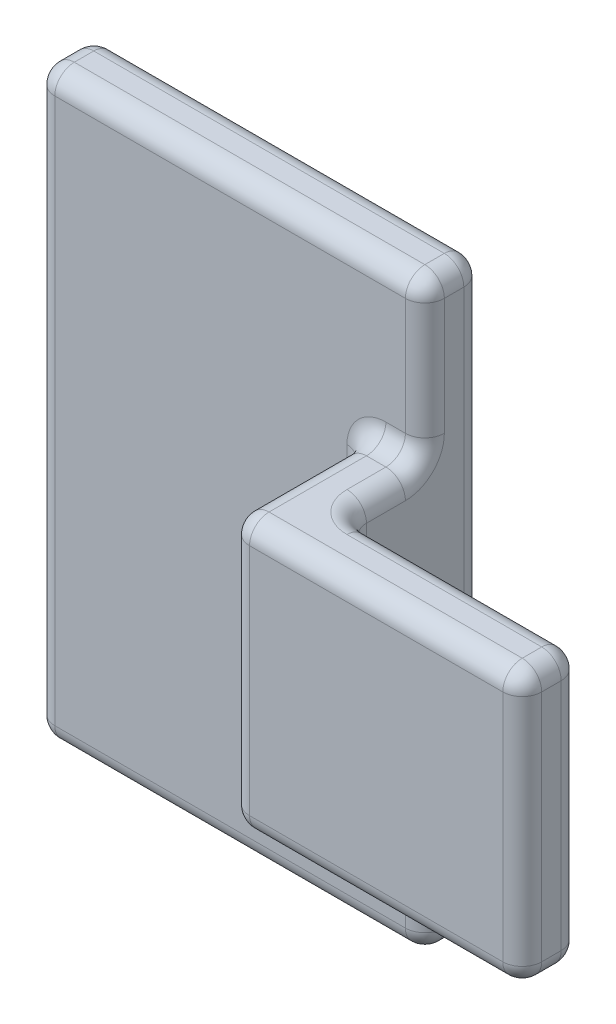
SolidWorks part; units mm, degrees
ref_plane "Front Plane" through (0, 0, 0) normal (0, 0, 1) x (1, 0, 0)
ref_plane "Top Plane" through (0, 0, 0) normal (0, 1, 0) x (1, 0, 0)
ref_plane "Right Plane" through (0, 0, 0) normal (1, 0, 0) x (0, 0, -1)
sketch "Sketch1" plane through (0, 0, 0) normal (0, 0, 1) x (1, 0, 0)
  line L0 (0, -30) -> (0, 0)
  line L3 (0, -30) -> (20, -30)
  line L4 (20, -30) -> (20, 0)
  line L5 (20, 0) -> (0, 0)
  line L6 (10, -7.5) -> (10, -22.5) construction
  line L7 (10, -15) -> (0, -15) construction
  line L8 (10, -15) -> (10, -30) construction
  circle A2 centre (10, -7.5) radius 2.25 construction
  circle A3 centre (10, -22.5) radius 2.25 construction
  dimension "D4" = 4.5
  dimension "D5" = 4.5
  dimension "D1" = 20
  dimension "D2" = 30
  dimension "D3" = 15
extrude "Boss-Extrude1" add sketch "Sketch1" along normal blind 3
ref_plane "Plane1" through (20, 0, 0) normal (-1, 0, 0) x (0, 0, 1)
sketch "Sketch3" plane through (20, 0, 0) normal (-1, 0, 0) x (0, 0, 1)
  line L0 (3, -8) -> (10, -8)
  line L1 (3, 0) -> (3, -30) construction
  line L2 (10, -8) -> (10, -22)
  line L3 (10, -22) -> (3, -22)
  line L4 (3, -22) -> (3, -8)
  dimension "D1" = 8
  dimension "D2" = 7
  dimension "D3" = 8
extrude "Boss-Extrude2" add sketch "Sketch3" along normal blind 3
sketch "Sketch4" plane through (17, 0, 0) normal (-1, 0, 0) x (0, 0, 1)
  line L0 (10, -8) -> (3, -8) construction
  line L1 (10, -22) -> (7, -22)
  line L2 (10, -22) -> (10, -8)
  line L3 (10, -8) -> (7, -8)
  line L4 (7, -22) -> (7, -8)
  dimension "D1" = 3
extrude "Boss-Extrude3" add sketch "Sketch4" against normal blind 15
ref_plane "Plane2" through (0, 0, 10) normal (0, 0, 1) x (1, 0, 0)
sketch "Sketch6" plane through (0, 0, 10) normal (0, 0, 1) x (1, 0, 0)
  line L1 (32, 14.1) -> (23, 14.1)
  line L2 (32, 14.1) -> (32, -44.1)
  line L3 (32, -44.1) -> (23, -44.1)
  line L4 (23, 14.1) -> (23, -44.1)
  dimension "D1" = 0
  dimension "D2" = 22.1
  dimension "D3" = 22.1
  dimension "D4" = 9
extrude "Boss-Extrude4" [suppressed] add sketch "Sketch6" against normal blind 2
sketch "Sketch7" [suppressed] plane through (0, 0, 21) normal (0, 0, -1) x (-1, 0, 0)
  line L2 (-38.6471, 43.1227) -> (-38.6471, 41.1227)
  line L5 (-38.6471, 43.1227) -> (-47.6471, 43.1227)
  line L6 (-47.6471, 43.1227) -> (-47.6471, 41.1227)
  line L7 (-47.6471, -35.8773) -> (-47.6471, 43.1227) construction
  line L8 (-47.6471, 41.1227) -> (-38.6471, 41.1227)
  dimension "D1" = 2
extrude "Boss-Extrude5" [suppressed] add sketch "Sketch7" along normal blind 18.4
sketch "Sketch9" [suppressed] plane through (0, 41.1227, 0) normal (0, -1, 0) x (1, 0, 0)
  line L2 (47.6471, 2.6) -> (47.6471, 4.6)
  line L5 (47.6471, 4.6) -> (41.6471, 4.6)
  line L6 (41.6471, 4.6) -> (41.6471, 2.6)
  line L7 (47.6471, 2.6) -> (38.6471, 2.6) construction
  line L8 (41.6471, 2.6) -> (47.6471, 2.6)
  dimension "D1" = 2
  dimension "D2" = 3
extrude "Boss-Extrude7" [suppressed] add sketch "Sketch9" along normal blind 3
mirror "Mirror2" [suppressed] about plane through (0, 0, 0) normal (0, 1, 0)
ref_plane "Plane3" [suppressed] through (38.6471, 0, 0) normal (-1, 0, 0) x (0, 0, 1)
sketch "Sketch10" [suppressed] plane through (38.6471, 0, 0) normal (-1, 0, 0) x (0, 0, 1)
  line L0 (23, -23.4) -> (15, -23.4)
  line L1 (23, -11) -> (23, 11) construction
  line L2 (15, -23.4) -> (15, -26.2)
  line L3 (15, -26.2) -> (23, -26.2)
  line L4 (23, -26.2) -> (23, -23.4)
  dimension "D1" = 8.5
  dimension "D2" = 5.7
  dimension "D3" = 8
sketch "Sketch11" plane through (20, 0, 0) normal (1, 0, 0) x (0, 0, -1)
  circle A0 centre (-19.6265, 5.2253) radius 1.25
  circle A1 centre (-19.6265, -4.7747) radius 1.175
  dimension "D1" = 2.5
  dimension "D2" = 2.35
  dimension "D3" = 10
extrude "Cut-Extrude1" [suppressed] cut sketch "Sketch11" against normal through all
fillet "Fillet1" radius 1 19 edges at (26, -8, 7) (26, -22, 7) (18.5, -8, 3) (18.5, -22, 3) (20, -8, 5) (20, -4, 3) (20, -26, 3) (20, -22, 5) (20, -15, 7) (32, -8, 8.5) (32, -15, 7) (32, -22, 8.5) (24.5, -8, 10) (32, -15, 10) (24.5, -22, 10) (17, -15, 3) (17, -8, 6.5) (17, -15, 10) (17, -22, 6.5)
fillet "Fillet2" radius 1 13 edges at (9.5, -30, 3) (10, -30, 0) (10, 0, 0) (9.5, 0, 3) (0, 0, 1.5) (0, -15, 3) (0, -30, 1.5) (0, -15, 0) (20, -30, 1) (20, 0, 1) (20, -15, 0) (19.7071, -30, 2.7071) (19.7071, 0, 2.7071)
